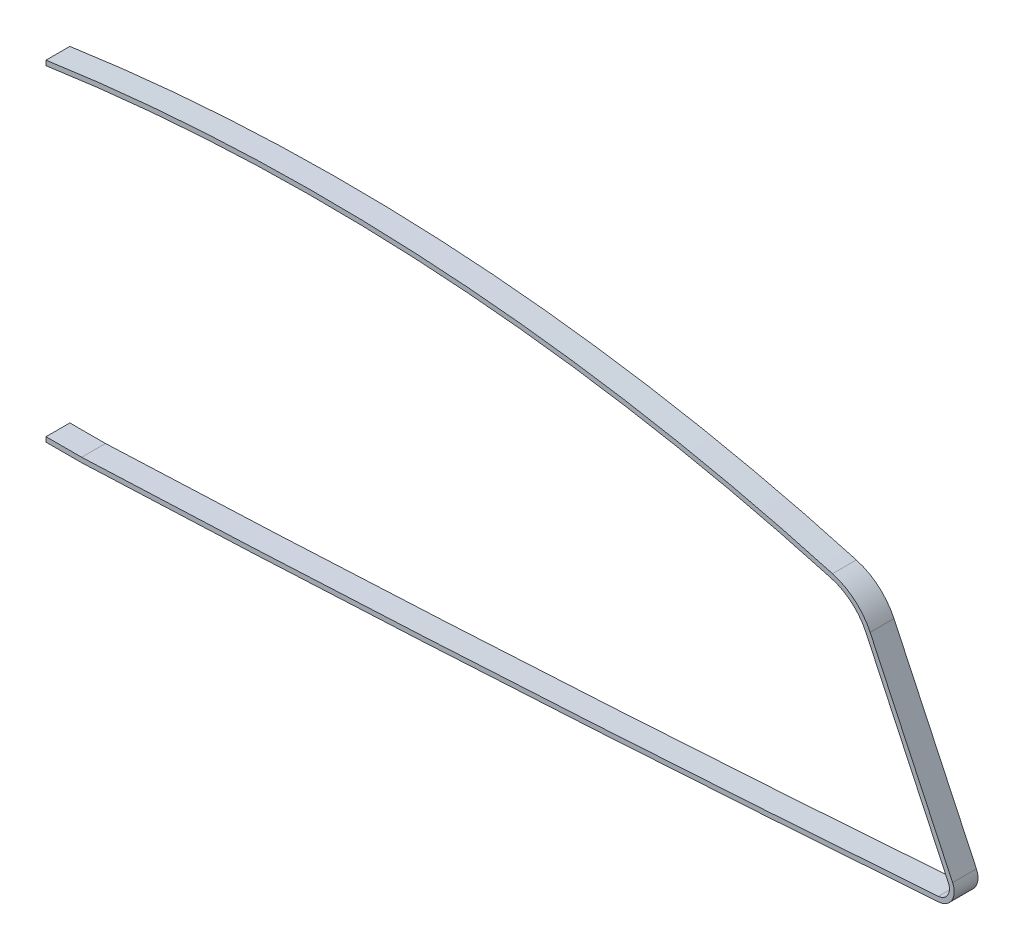
SolidWorks part; units mm, degrees
ref_plane "Front Plane" through (0, 0, 0) normal (0, 0, 1) x (1, 0, 0)
ref_plane "Top Plane" through (0, 0, 0) normal (0, 1, 0) x (1, 0, 0)
ref_plane "Right Plane" through (0, 0, 0) normal (1, 0, 0) x (0, 0, -1)
ref_plane "Plane1" through (0, 0, -4) normal (0, 0, 1) x (1, 0, 0)
sketch "BASE DASH IF PROFILE" plane through (0, 0, -4) normal (0, 0, 1) x (1, 0, 0)
  line L0 (-300, 17.25) -> (-9.9069, 17.25)
  line L1 (-6, 3.25) -> (6, 3.25) construction
  line L2 (-291, 3.25) -> (-279, 3.25) construction
  line L3 (-291, -3.25) -> (-279, -3.25) construction
  line L4 (-284.25, -77) -> (-284.25, -89) construction
  line L5 (-293.2421, -117) -> (-30.25, -117)
  line L6 (-277.75, -77) -> (-277.75, -89) construction
  line L7 (31.75, -81) -> (31.75, -93) construction
  line L8 (31.75, -93) -> (38.25, -93) construction
  line L9 (218.75, -90) -> (225.25, -90) construction
  line L10 (374.75, -80) -> (381.25, -80) construction
  line L11 (381.25, -68) -> (381.25, -80) construction
  line L12 (332, -9.75) -> (344, -9.75) construction
  line L13 (344, -9.75) -> (344, -16.25) construction
  line L14 (184, 13.25) -> (184, 6.75) construction
  line L15 (32, 5.25) -> (44, 5.25) construction
  line L16 (400.3845, -86.8478) -> (365.7956, -13.2095)
  line L17 (172, 13.25) -> (184, 13.25) construction
  line L18 (-30.25, -117) -> (35, -117)
  arc A0 (-300, 17.25) -> (-310, 18.25) centre (-300, 67.75) cw
  arc A1 (-310, 18.25) -> (-293.25, -103) centre (-793.197, -110.2829) cw
  arc A2 (-293.2421, -117) -> (-293.25, -103) centre (-793.197, -110.2829) ccw
  arc A3 (401, -89) -> (394.5578, -96.8053) centre (394.0486, -89.8238) cw
  arc A4 (394.5578, -96.8053) -> (35, -117) centre (-390.0429, 10661.6695) cw
  arc A5 (401, -89) -> (400.3845, -86.8478) centre (394.0486, -89.8238) ccw
  arc A6 (-5.465, 17.6478) -> (349.996, 0.2111) centre (134.6308, -758.2832) cw
  arc A7 (365.7956, -13.2095) -> (349.996, 0.2111) centre (343.1675, -23.8383) ccw
  arc A8 (-5.465, 17.6478) -> (-9.9069, 17.25) centre (-9.9069, 42.25) cw
  point P9 (-285, 3.25)
  point P10 (-310, 18.25)
  point P11 (-285, -3.25)
  point P14 (-293.25, -103)
  point P17 (-284.25, -83)
  point P24 (-277.75, -83)
  point P29 (35, -117)
  point P32 (35, -93)
  point P33 (222, -108)
  point P36 (222, -90)
  point P37 (378, -98)
  point P40 (378, -80)
  point P41 (401, -89)
  point P43 (381.25, -74)
  point P44 (361, -3)
  point P47 (338, -9.75)
  point P50 (344, -13)
  point P51 (178, 29)
  point P54 (184, 10)
  point P55 (38, 24.25)
  point P58 (38, 5.25)
  point P70 (361, -3)
  point P75 (178, 13.25)
  dimension "D8" = 500
  dimension "D20" = 7
  dimension "D21" = 25
  dimension "D22" = 25
  dimension "D1" = 14
  dimension "D3" = 15
  dimension "D4" = 25
  dimension "D5" = 15
  dimension "D6" = 9
  dimension "D7" = 20
  dimension "D9" = 34
  dimension "D10" = 62
  dimension "D11" = 24
  dimension "D12" = 18
  dimension "D13" = 18
  dimension "D14" = 23
  dimension "D15" = 15
  dimension "D16" = 23
  dimension "D17" = 10
  dimension "D18" = 19
  dimension "D19" = 19
sketch "Sketch2" plane through (0, 0, -4) normal (0, 0, 1) x (1, 0, 0)
  line L0 (-300, 17.25) -> (-9.9069, 17.25) construction
  line L1 (400.3845, -86.8478) -> (365.7956, -13.2095) construction
  line L2 (-30.25, -117) -> (35, -117) construction
  line L3 (-293.2421, -117) -> (-30.25, -117) construction
  line L4 (-300, 17.25) -> (-9.9069, 17.25)
  line L5 (400.3845, -86.8478) -> (365.7956, -13.2095)
  line L6 (-30.25, -117) -> (35, -117)
  line L7 (-293.2421, -117) -> (-30.25, -117)
  line L8 (-300, 15.25) -> (-9.9069, 15.25)
  line L9 (398.5743, -87.6981) -> (363.9853, -14.0598)
  line L10 (-30.25, -115) -> (34.9606, -115)
  line L11 (-291.2191, -115) -> (-30.25, -115)
  arc A0 (-9.9069, 17.25) -> (-5.465, 17.6478) centre (-9.9069, 42.25) ccw construction
  arc A1 (349.996, 0.2111) -> (-5.465, 17.6478) centre (134.6308, -758.2832) ccw construction
  arc A2 (365.7956, -13.2095) -> (349.996, 0.2111) centre (343.1675, -23.8383) ccw construction
  arc A3 (401, -89) -> (400.3845, -86.8478) centre (394.0486, -89.8238) ccw construction
  arc A4 (394.5578, -96.8053) -> (401, -89) centre (394.0486, -89.8238) ccw construction
  arc A5 (35, -117) -> (394.5578, -96.8053) centre (-390.0429, 10661.6695) ccw construction
  arc A6 (-293.2421, -117) -> (-293.25, -103) centre (-793.197, -110.2829) ccw construction
  arc A7 (-293.25, -103) -> (-310, 18.25) centre (-793.197, -110.2829) ccw construction
  arc A8 (-310, 18.25) -> (-300, 17.25) centre (-300, 67.75) ccw construction
  arc A9 (-9.9069, 17.25) -> (-5.465, 17.6478) centre (-9.9069, 42.25) ccw
  arc A10 (349.996, 0.2111) -> (-5.465, 17.6478) centre (134.6308, -758.2832) ccw
  arc A11 (365.7956, -13.2095) -> (349.996, 0.2111) centre (343.1675, -23.8383) ccw
  arc A12 (401, -89) -> (400.3845, -86.8478) centre (394.0486, -89.8238) ccw
  arc A13 (394.5578, -96.8053) -> (401, -89) centre (394.0486, -89.8238) ccw
  arc A14 (35, -117) -> (394.5578, -96.8053) centre (-390.0429, 10661.6695) ccw
  arc A15 (-293.2421, -117) -> (-293.25, -103) centre (-793.197, -110.2829) ccw
  arc A16 (-293.25, -103) -> (-310, 18.25) centre (-793.197, -110.2829) ccw
  arc A17 (-310, 18.25) -> (-300, 17.25) centre (-300, 67.75) ccw
  arc A18 (-9.9069, 15.25) -> (-5.1096, 15.6796) centre (-9.9069, 42.25) ccw
  arc A19 (349.4497, -1.7129) -> (-5.1096, 15.6796) centre (134.6308, -758.2832) ccw
  arc A20 (363.9853, -14.0598) -> (349.4497, -1.7129) centre (343.1675, -23.8383) ccw
  arc A21 (399.0139, -89.2354) -> (398.5743, -87.6981) centre (394.0486, -89.8238) ccw
  arc A22 (394.4123, -94.8106) -> (399.0139, -89.2354) centre (394.0486, -89.8238) ccw
  arc A23 (34.9606, -115) -> (394.4123, -94.8106) centre (-390.0429, 10661.6695) ccw
  arc A24 (-291.2191, -115) -> (-291.2502, -102.9709) centre (-793.197, -110.2829) ccw
  arc A25 (-291.2502, -102.9709) -> (-307.2772, 15.7568) centre (-793.197, -110.2829) ccw
  arc A26 (-307.2772, 15.7568) -> (-300, 15.25) centre (-300, 67.75) ccw
  dimension "D1" = 2
extrude "Boss-Extrude1" add sketch "Sketch2" along normal blind 10
ref_plane "Plane2" through (20, 0, 0) normal (1, 0, 0) x (0, 0, -1)
sketch "Sketch3" plane through (20, 0, 0) normal (1, 0, 0) x (0, 0, -1)
  line L1 (-100.4265, 88.1761) -> (108.3196, 88.1761)
  line L2 (-100.4265, 88.1761) -> (-100.4265, -186.3596)
  line L3 (-100.4265, -186.3596) -> (108.3196, -186.3596)
  line L4 (108.3196, 88.1761) -> (108.3196, -186.3596)
  point P4 (108.3196, -186.3596)
extrude "Cut-Extrude1" cut sketch "Sketch3" against normal through all
